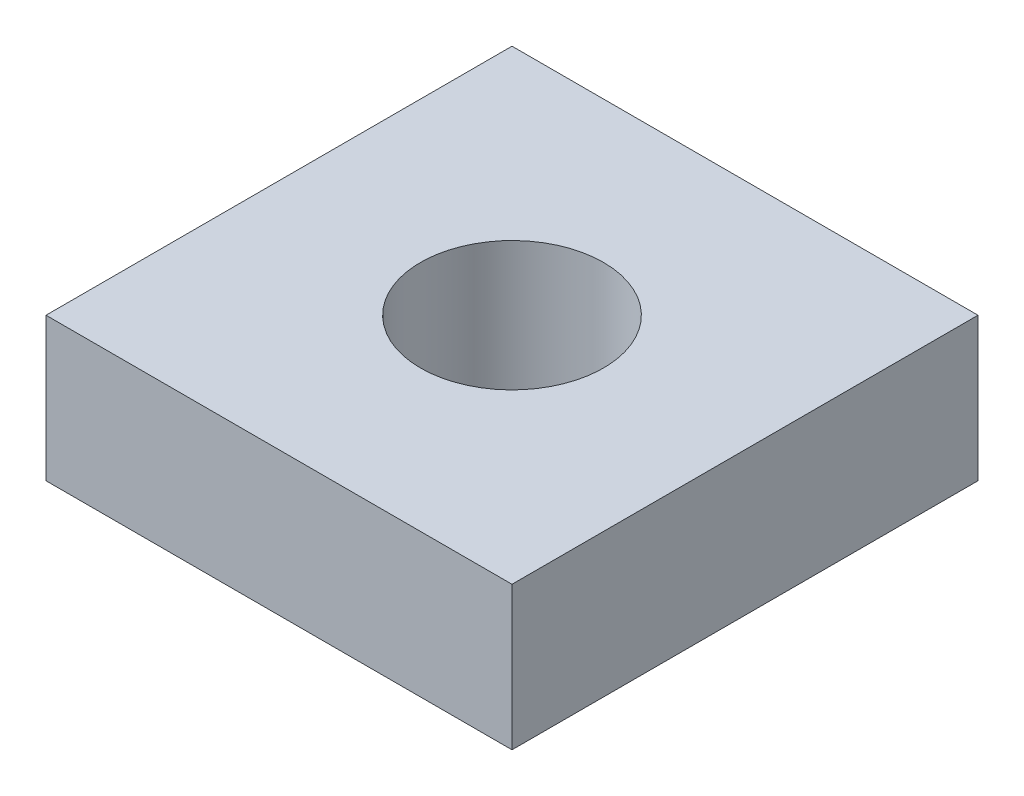
SolidWorks part; units mm, degrees
ref_plane "Ebene vorne" through (0, 0, 0) normal (0, 0, 1) x (1, 0, 0)
ref_plane "Ebene oben" through (0, 0, 0) normal (0, 1, 0) x (1, 0, 0)
ref_plane "Ebene rechts" through (0, 0, 0) normal (1, 0, 0) x (0, 0, -1)
sketch "Skizze1" plane through (0, 0, 0) normal (0, 0, 1) x (1, 0, 0)
  line L9 (0, 0) -> (13, 0)
  line L10 (0, 0) -> (0, 4)
  line L11 (0, 4) -> (13, 4)
  line L12 (13, 0) -> (13, 4)
  dimension "D1" = 13
  dimension "D2" = 4
extrude "Aufsatz-Linear austragen1" add sketch "Skizze1" along normal blind 13
hole_wizard "1/4-20 Gewindebohrung2" positions "Skizze6" profile "Skizze7" tap size "1/4-20" standard "ANSI Inch" end condition through all
sketch "Skizze6" plane through (0, 4, 0) normal (0, 1, 0) x (1, 0, 0)
  line L0 (0, -13) -> (0, 0) construction
  line L1 (13, -13) -> (0, -13) construction
  point P0 (6.5, -6.5)
  dimension "D1" = 6.5
  dimension "D2" = 6.5
sketch "Skizze7" plane through (6.5, 4, 6.5) normal (1, 0, 0) x (0, 0, 1)
  line L0 (0, 0) -> (0, 4)
  line L1 (0, 4) -> (2.5527, 4)
  line L2 (2.5527, 4) -> (2.5527, 0)
  line L5 (2.5527, 0) -> (0, 0)
  line L11 (0, -6.35) -> (0, 107.95) construction
  dimension "Bohrerdurchmesser" = 5.1054
  dimension "Bohrungstiefe" = 4
cosmetic thread "Bohrungsgewinde2" parameters "D2"=6.35
